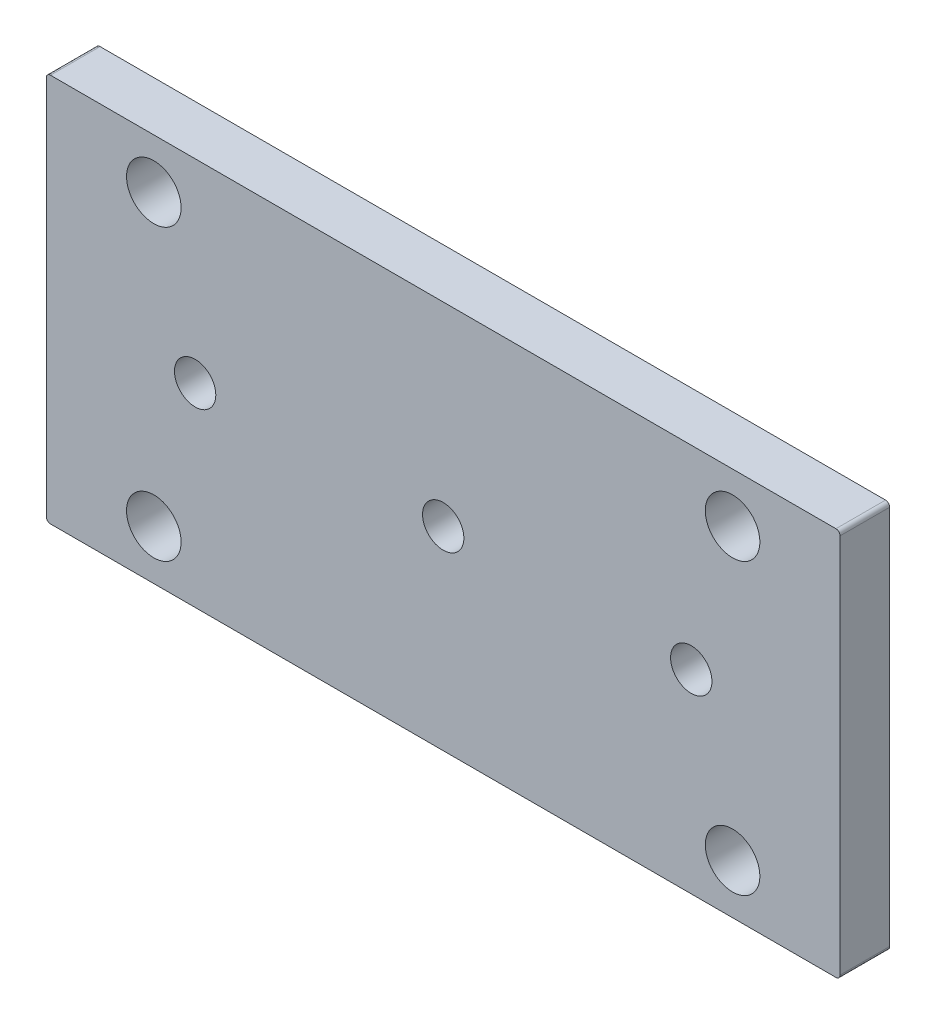
SolidWorks part; units mm, degrees
ref_plane "前视基准面" through (0, 0, 0) normal (0, 0, 1) x (1, 0, 0)
ref_plane "上视基准面" through (0, 0, 0) normal (0, 1, 0) x (1, 0, 0)
ref_plane "右视基准面" through (0, 0, 0) normal (1, 0, 0) x (0, 0, -1)
other "Configuration Table"
sketch "草图1" plane through (0, 0, 0) normal (0, 0, 1) x (1, 0, 0)
  line L0 (0, 0) -> (96, 0)
  line L1 (96, 0) -> (96, -47)
  line L2 (96, -47) -> (0, -47)
  line L3 (0, -47) -> (0, 0)
  dimension "D1" = 96
  dimension "D2" = 47
extrude "凸台-拉伸1" add sketch "草图1" along normal blind 6
sketch "草图2" plane through (0, 0, 6) normal (0, 0, 1) x (1, 0, 0)
  line L0 (96, -23.5) -> (0, -23.5)
  line L1 (96, -47) -> (96, 0) construction
  line L2 (0, 0) -> (0, -47) construction
  line L3 (48, 0) -> (48, -47)
  line L4 (96, 0) -> (0, 0) construction
  line L5 (0, -47) -> (96, -47) construction
  line L6 (48, -23.5) -> (48, -12)
  circle A0 centre (83, -6) radius 3.3
  circle A1 centre (83, -41) radius 3.3
  circle A2 centre (13, -41) radius 3.3
  circle A3 centre (13, -6) radius 3.3
  circle A5 centre (48, -23.5) radius 3
  circle A6 centre (78, -23.5) radius 3
  circle A7 centre (18, -23.5) radius 3
  dimension "D1" = 35
  dimension "D3" = 30
  dimension "D4" = 30
  dimension "D2" = 17.5
extrude "切除-拉伸1" cut sketch "草图2" against normal blind 10 contours A0 | A1 | A2 | A3
hole_wizard "M6 螺纹孔2" positions "草图15" profile "草图16" tap size "M6" standard "GB" end condition through all
sketch "草图15" plane through (0, 0, 6) normal (0, 0, 1) x (1, 0, 0)
  point P0 (18, -23.5)
  point P3 (48, -23.5)
  point P6 (78, -23.5)
cosmetic thread "孔螺蚊线5" parameters "D2"=6
cosmetic thread "孔螺蚊线6" parameters "D2"=6
cosmetic thread "孔螺蚊线7" parameters "D2"=6
sketch "草图16" plane through (18, -23.5, 6) normal (1, 0, 0) x (0, -1, 0)
  line L0 (0, 0) -> (0, 6)
  line L1 (0, 6) -> (2.5, 6)
  line L2 (2.5, 6) -> (2.5, 0)
  line L5 (2.5, 0) -> (0, 0)
  line L11 (0, -6.35) -> (0, 107.95) construction
  dimension "通孔螺纹孔钻头直径" = 5
  dimension "通孔螺纹孔钻头深度" = 6
fillet "圆角1" radius 0.5 4 edges at (0, 0, 3) (96, 0, 3) (96, -47, 3) (0, -47, 3)
